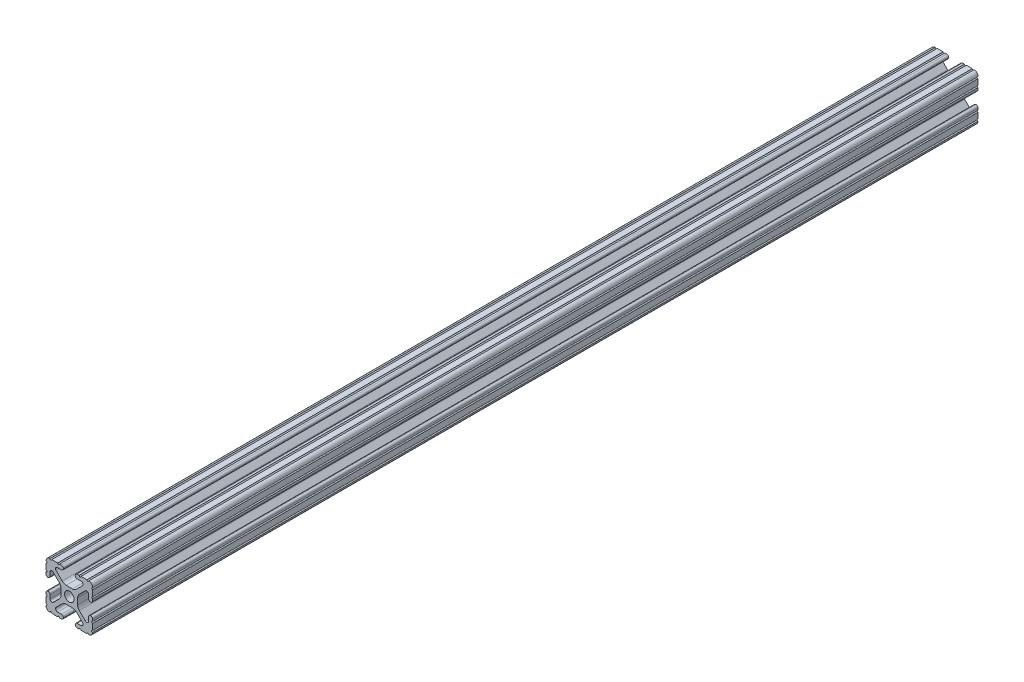
SolidWorks part; units mm, degrees
ref_plane "Front Plane" through (0, 0, 0) normal (0, 0, 1) x (1, 0, 0)
ref_plane "Top Plane" through (0, 0, 0) normal (0, 1, 0) x (1, 0, 0)
ref_plane "Right Plane" through (0, 0, 0) normal (1, 0, 0) x (0, 0, -1)
sketch "Sketch1" plane through (0, 0, 0) normal (0, 0, 1) x (1, 0, 0)
  line L88 (-7.1797, -8.6452) -> (-3.9523, -5.4237)
  line L89 (-1.7093, -4.4958) -> (1.7093, -4.4958)
  line L90 (3.9523, -5.4237) -> (7.1797, -8.6452)
  line L91 (6.4164, -10.4902) -> (4.2875, -10.4902)
  line L92 (3.2385, -11.5392) -> (3.2385, -11.651)
  line L93 (4.2875, -12.7) -> (5.3171, -12.7)
  line L94 (6.3331, -12.7) -> (9.5504, -12.7)
  line L95 (12.7, -9.5504) -> (12.7, -6.3331)
  line L96 (12.7, -5.3171) -> (12.7, -4.2875)
  line L97 (11.651, -3.2385) -> (11.5392, -3.2385)
  line L98 (10.4902, -4.2875) -> (10.4902, -6.4021)
  line L99 (8.7371, -7.1294) -> (5.441, -3.8408)
  line L100 (4.5085, -1.5932) -> (4.5085, 1.5932)
  line L101 (5.441, 3.8408) -> (8.7371, 7.1294)
  line L102 (10.4902, 6.4021) -> (10.4902, 4.2875)
  line L103 (11.5392, 3.2385) -> (11.651, 3.2385)
  line L104 (12.7, 4.2875) -> (12.7, 5.3171)
  line L105 (12.7, 6.3331) -> (12.7, 9.5504)
  line L106 (9.5504, 12.7) -> (6.3331, 12.7)
  line L107 (5.3171, 12.7) -> (4.2875, 12.7)
  line L108 (3.2385, 11.651) -> (3.2385, 11.5392)
  line L109 (4.2875, 10.4902) -> (6.4768, 10.4902)
  line L110 (7.207, 8.7244) -> (3.8983, 5.4232)
  line L111 (1.6558, 4.4958) -> (-1.6558, 4.4958)
  line L112 (-3.8983, 5.4232) -> (-7.207, 8.7244)
  line L113 (-6.4768, 10.4902) -> (-4.2875, 10.4902)
  line L114 (-3.2385, 11.5392) -> (-3.2385, 11.651)
  line L115 (-4.2875, 12.7) -> (-5.3171, 12.7)
  line L116 (-6.3331, 12.7) -> (-9.5504, 12.7)
  line L117 (-12.7, 9.5504) -> (-12.7, 6.3331)
  line L118 (-12.7, 5.3171) -> (-12.7, 4.2875)
  line L119 (-11.651, 3.2385) -> (-11.5392, 3.2385)
  line L120 (-10.4902, 4.2875) -> (-10.4902, 6.4021)
  line L121 (-8.7371, 7.1294) -> (-5.441, 3.8408)
  line L122 (-4.5085, 1.5932) -> (-4.5085, -1.5932)
  line L123 (-5.441, -3.8408) -> (-8.7371, -7.1294)
  line L124 (-10.4902, -6.4021) -> (-10.4902, -4.2875)
  line L125 (-11.5392, -3.2385) -> (-11.651, -3.2385)
  line L126 (-12.7, -4.2875) -> (-12.7, -5.3171)
  line L127 (-12.7, -6.3331) -> (-12.7, -9.5504)
  line L128 (-9.5504, -12.7) -> (-6.3331, -12.7)
  line L129 (-5.3171, -12.7) -> (-4.2875, -12.7)
  line L130 (-3.2385, -11.651) -> (-3.2385, -11.5392)
  line L131 (-4.2875, -10.4902) -> (-6.4164, -10.4902)
  circle A1 centre (0, 0) radius 2.6035
  arc A104 (-7.1797, -8.6452) -> (-6.4164, -10.4902) centre (-6.4164, -9.4098) ccw
  arc A105 (-1.7093, -4.4958) -> (-3.9523, -5.4237) centre (-1.7093, -7.6708) ccw
  arc A106 (3.9523, -5.4237) -> (1.7093, -4.4958) centre (1.7093, -7.6708) ccw
  arc A107 (6.4164, -10.4902) -> (7.1797, -8.6452) centre (6.4164, -9.4098) ccw
  arc A108 (4.2875, -10.4902) -> (3.2385, -11.5392) centre (4.2875, -11.5392) ccw
  arc A109 (3.2385, -11.651) -> (4.2875, -12.7) centre (4.2875, -11.651) ccw
  arc A110 (6.3331, -12.7) -> (5.3171, -12.7) centre (5.8251, -12.7) ccw
  arc A111 (10.5664, -12.6998) -> (9.5504, -12.7) centre (10.0584, -12.7) ccw
  arc A112 (10.5664, -12.6998) -> (12.6998, -10.5664) centre (10.5918, -10.5918) ccw
  arc A113 (12.7, -9.5504) -> (12.6998, -10.5664) centre (12.7, -10.0584) ccw
  arc A114 (12.7, -5.3171) -> (12.7, -6.3331) centre (12.7, -5.8251) ccw
  arc A115 (12.7, -4.2875) -> (11.651, -3.2385) centre (11.651, -4.2875) ccw
  arc A116 (11.5392, -3.2385) -> (10.4902, -4.2875) centre (11.5392, -4.2875) ccw
  arc A117 (8.7371, -7.1294) -> (10.4902, -6.4021) centre (9.4628, -6.4021) ccw
  arc A118 (4.5085, -1.5932) -> (5.441, -3.8408) centre (7.6835, -1.5932) ccw
  arc A119 (5.441, 3.8408) -> (4.5085, 1.5932) centre (7.6835, 1.5932) ccw
  arc A120 (10.4902, 6.4021) -> (8.7371, 7.1294) centre (9.4628, 6.4021) ccw
  arc A121 (10.4902, 4.2875) -> (11.5392, 3.2385) centre (11.5392, 4.2875) ccw
  arc A122 (11.651, 3.2385) -> (12.7, 4.2875) centre (11.651, 4.2875) ccw
  arc A123 (12.7, 6.3331) -> (12.7, 5.3171) centre (12.7, 5.8251) ccw
  arc A124 (12.6998, 10.5664) -> (12.7, 9.5504) centre (12.7, 10.0584) ccw
  arc A125 (12.6998, 10.5664) -> (10.5664, 12.6998) centre (10.5918, 10.5918) ccw
  arc A126 (9.5504, 12.7) -> (10.5664, 12.6998) centre (10.0584, 12.7) ccw
  arc A127 (5.3171, 12.7) -> (6.3331, 12.7) centre (5.8251, 12.7) ccw
  arc A128 (4.2875, 12.7) -> (3.2385, 11.651) centre (4.2875, 11.651) ccw
  arc A129 (3.2385, 11.5392) -> (4.2875, 10.4902) centre (4.2875, 11.5392) ccw
  arc A130 (7.207, 8.7244) -> (6.4768, 10.4902) centre (6.4768, 9.4563) ccw
  arc A131 (1.6558, 4.4958) -> (3.8983, 5.4232) centre (1.6558, 7.6708) ccw
  arc A132 (-3.8983, 5.4232) -> (-1.6558, 4.4958) centre (-1.6558, 7.6708) ccw
  arc A133 (-6.4768, 10.4902) -> (-7.207, 8.7244) centre (-6.4768, 9.4563) ccw
  arc A134 (-4.2875, 10.4902) -> (-3.2385, 11.5392) centre (-4.2875, 11.5392) ccw
  arc A135 (-3.2385, 11.651) -> (-4.2875, 12.7) centre (-4.2875, 11.651) ccw
  arc A136 (-6.3331, 12.7) -> (-5.3171, 12.7) centre (-5.8251, 12.7) ccw
  arc A137 (-10.5664, 12.6998) -> (-9.5504, 12.7) centre (-10.0584, 12.7) ccw
  arc A138 (-10.5664, 12.6998) -> (-12.6998, 10.5664) centre (-10.5918, 10.5918) ccw
  arc A139 (-12.7, 9.5504) -> (-12.6998, 10.5664) centre (-12.7, 10.0584) ccw
  arc A140 (-12.7, 5.3171) -> (-12.7, 6.3331) centre (-12.7, 5.8251) ccw
  arc A141 (-12.7, 4.2875) -> (-11.651, 3.2385) centre (-11.651, 4.2875) ccw
  arc A142 (-11.5392, 3.2385) -> (-10.4902, 4.2875) centre (-11.5392, 4.2875) ccw
  arc A143 (-8.7371, 7.1294) -> (-10.4902, 6.4021) centre (-9.4628, 6.4021) ccw
  arc A144 (-4.5085, 1.5932) -> (-5.441, 3.8408) centre (-7.6835, 1.5932) ccw
  arc A145 (-5.441, -3.8408) -> (-4.5085, -1.5932) centre (-7.6835, -1.5932) ccw
  arc A146 (-10.4902, -6.4021) -> (-8.7371, -7.1294) centre (-9.4628, -6.4021) ccw
  arc A147 (-10.4902, -4.2875) -> (-11.5392, -3.2385) centre (-11.5392, -4.2875) ccw
  arc A148 (-11.651, -3.2385) -> (-12.7, -4.2875) centre (-11.651, -4.2875) ccw
  arc A149 (-12.7, -6.3331) -> (-12.7, -5.3171) centre (-12.7, -5.8251) ccw
  arc A150 (-12.6998, -10.5664) -> (-12.7, -9.5504) centre (-12.7, -10.0584) ccw
  arc A151 (-12.6998, -10.5664) -> (-10.5664, -12.6998) centre (-10.5918, -10.5918) ccw
  arc A152 (-9.5504, -12.7) -> (-10.5664, -12.6998) centre (-10.0584, -12.7) ccw
  arc A153 (-5.3171, -12.7) -> (-6.3331, -12.7) centre (-5.8251, -12.7) ccw
  arc A154 (-4.2875, -12.7) -> (-3.2385, -11.651) centre (-4.2875, -11.651) ccw
  arc A155 (-3.2385, -11.5392) -> (-4.2875, -10.4902) centre (-4.2875, -11.5392) ccw
extrude "Boss-Extrude1" add sketch "Sketch1" along normal mid plane 609.6
sketch "Sketch2" plane through (0, 0, -304.8) normal (0, 0, -1) x (-1, 0, 0)
  circle A0 centre (0, 0) radius 22.4536
extrude "Cut-Extrude1" cut sketch "Sketch2" against normal blind 127
